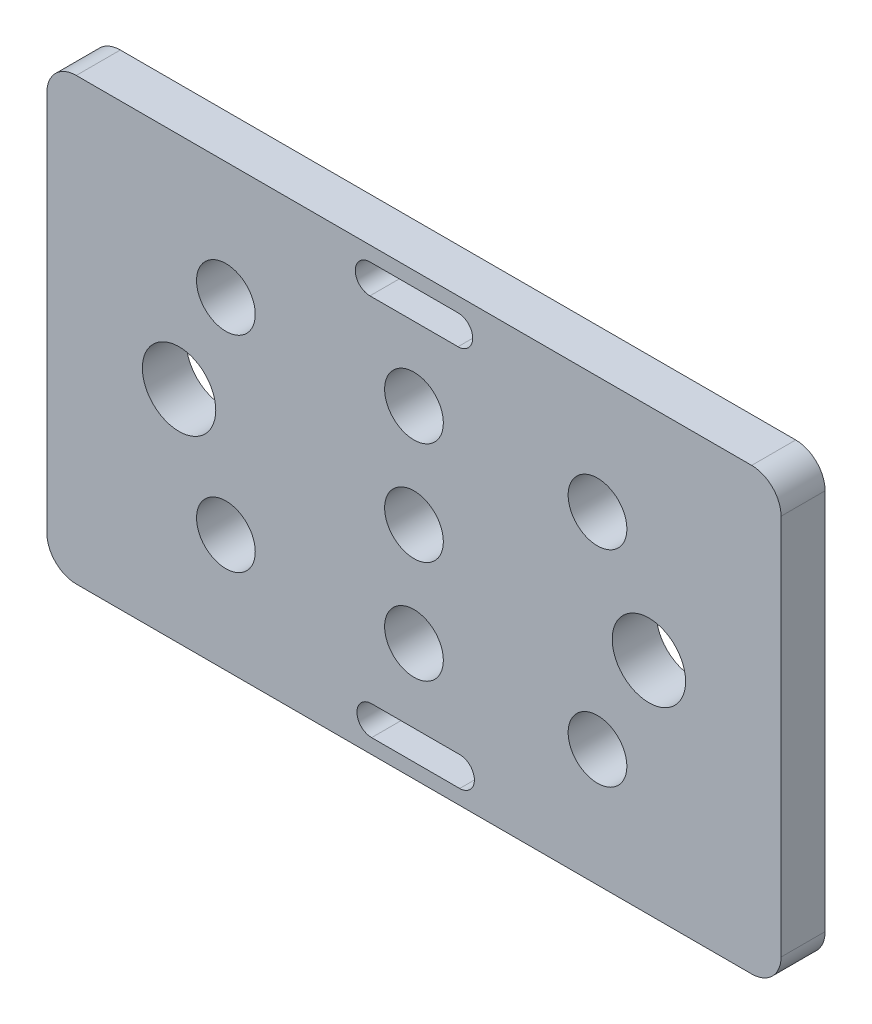
SolidWorks part; units mm, degrees
ref_plane "Front Plane" through (0, 0, 0) normal (0, 0, 1) x (1, 0, 0)
ref_plane "Top Plane" through (0, 0, 0) normal (0, 1, 0) x (1, 0, 0)
ref_plane "Right Plane" through (0, 0, 0) normal (1, 0, 0) x (0, 0, -1)
sketch "Model" plane through (0, 0, 0) normal (0, 0, 1) x (1, 0, 0)
  line L0 (-21.8848, 1) -> (-27.8848, 1)
  line L1 (-27.8848, 3) -> (-21.8848, 3)
  line L2 (-28, 28.9998) -> (-22, 28.9998)
  line L3 (-22, 26.9998) -> (-28, 26.9998)
  line L4 (-2, 30) -> (-48, 30)
  line L5 (-50, 28) -> (-50, 2)
  line L6 (-48, 0) -> (-2, 0)
  line L7 (0, 2) -> (0, 28)
  circle A0 centre (-25, 15) radius 2
  circle A1 centre (-37.8101, 8) radius 2
  circle A2 centre (-12.5, 8) radius 2
  circle A3 centre (-37.8101, 22) radius 2
  circle A4 centre (-12.5, 22) radius 2
  circle A5 centre (-25, 8) radius 2
  circle A6 centre (-25, 22) radius 2
  circle A7 centre (-9, 15) radius 2.5
  circle A8 centre (-41, 15) radius 2.5
  arc A9 (-21.8848, 1) -> (-21.8848, 3) centre (-21.8848, 2) ccw
  arc A10 (-27.8848, 3) -> (-27.8848, 1) centre (-27.8848, 2) ccw
  arc A11 (-28, 28.9998) -> (-28, 26.9998) centre (-28, 27.9998) ccw
  arc A12 (-22, 26.9998) -> (-22, 28.9998) centre (-22, 27.9998) ccw
  arc A13 (0, 28) -> (-2, 30) centre (-2, 28) ccw
  arc A14 (-48, 30) -> (-50, 28) centre (-48, 28) ccw
  arc A15 (-50, 2) -> (-48, 0) centre (-48, 2) ccw
  arc A16 (-2, 0) -> (0, 2) centre (-2, 2) ccw
extrude "Boss-Extrude1" add sketch "Model" along normal blind 3
